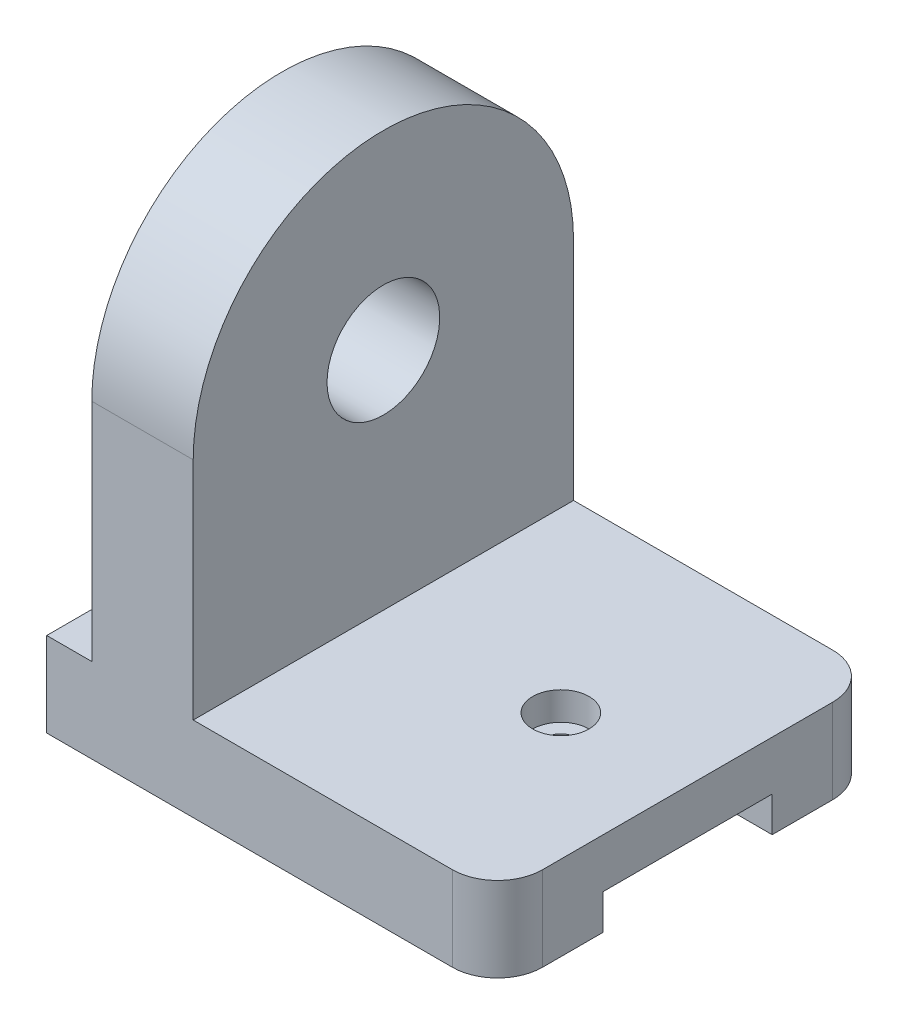
SolidWorks part; units mm, degrees
ref_plane "前视基准面" through (0, 0, 0) normal (0, 0, 1) x (1, 0, 0)
ref_plane "上视基准面" through (0, 0, 0) normal (0, 1, 0) x (1, 0, 0)
ref_plane "右视基准面" through (0, 0, 0) normal (1, 0, 0) x (0, 0, -1)
other "Configuration Table"
sketch "草图1" plane through (0, 0, 0) normal (0, 1, 0) x (1, 0, 0)
  line L1 (0, 0) -> (288, 0)
  line L2 (0, 0) -> (0, -270)
  line L3 (0, -270) -> (288, -270)
  line L4 (320, -32) -> (320, -238)
  arc A0 (288, -270) -> (320, -238) centre (288, -238) ccw
  arc A1 (288, 0) -> (320, -32) centre (288, -32) cw
  point P7 (320, -270)
  dimension "D3" = 32
  dimension "D1" = 320
  dimension "D2" = 270
extrude "凸台-拉伸1" add sketch "草图1" along normal blind 60
sketch "草图2" plane through (0, 0, 0) normal (0, -1, 0) x (1, 0, 0)
  line L0 (320, 238) -> (320, 32) construction
  line L1 (320, 135) -> (175.553, 135) construction
  line L2 (230, 195) -> (320, 195)
  line L3 (320, 195) -> (320, 75)
  line L4 (320, 75) -> (230, 75)
  arc A0 (230, 195) -> (230, 75) centre (230, 135) ccw
  dimension "D1" = 120
  dimension "D2" = 90
extrude "切除-拉伸1" cut sketch "草图2" against normal blind 25 and the other way through all
sketch "草图6" plane through (0, 60, 0) normal (0, 1, 0) x (1, 0, 0)
  arc A0 (230, -75) -> (230, -195) centre (230, -135) ccw construction
  arc A1 (230, -75) -> (230, -195) centre (230, -135) ccw
  point P0 (230, -135)
hole_wizard "孔1" positions "草图6" profile "草图7" legacy end condition through all
sketch "草图7" plane through (230, 60, 135) normal (1, 0, 0) x (0, 0, 1)
  line L0 (0, 0) -> (0, 60)
  line L1 (0, 60) -> (10, 60)
  line L2 (10, 60) -> (10, 20)
  line L3 (10, 20) -> (20, 20)
  line L4 (20, 20) -> (20, 0)
  line L5 (20, 0) -> (0, 0)
  line L6 (0, 110) -> (0, -10) construction
  dimension "直径" = 20
  dimension "深度" = 60
  dimension "柱坑直径" = 40
  dimension "柱坑深度" = 20
sketch "草图8" plane through (0, 0, 0) normal (-1, 0, 0) x (0, 0, 1)
  line L0 (135, 60) -> (135, 228.9276) construction
  line L1 (0, 60) -> (270, 60) construction
  line L2 (0, 60) -> (0, 220)
  line L3 (270, 60) -> (270, 220)
  line L4 (270, 220) -> (0, 220)
  line L5 (0, 60) -> (270, 60)
  arc A3 (270, 220) -> (0, 220) centre (135, 220) ccw
  dimension "D1" = 160
extrude "凸台-拉伸3" add sketch "草图8" against normal blind 72 from offset 32 offset against normal yes
sketch "草图10" plane through (32, 0, 0) normal (-1, 0, 0) x (0, 0, 1)
  line L0 (15, 220) -> (15, 75)
  line L1 (15, 75) -> (255, 75)
  line L2 (255, 75) -> (255, 220)
  line L3 (0, 220) -> (0, 60)
  line L4 (0, 60) -> (270, 60)
  line L5 (270, 60) -> (270, 220)
  line L6 (0, 220) -> (0, 60)
  line L7 (0, 60) -> (270, 60)
  line L8 (270, 60) -> (270, 220)
  arc A0 (255, 220) -> (15, 220) centre (135, 220) ccw
  arc A1 (270, 220) -> (0, 220) centre (135, 220) ccw
  arc A2 (270, 220) -> (0, 220) centre (135, 220) ccw
  circle A3 centre (135, 220) radius 40
  circle A4 centre (135, 220) radius 80
  dimension "D3" = 160
  dimension "D4" = 80
  dimension "D1" = 0
  dimension "D2" = 15
extrude "切除-拉伸3" cut sketch "草图10" against normal through all both and the other way through all contours A3
sketch "草图12" plane through (32, 0, 0) normal (-1, 0, 0) x (0, 0, 1)
  line L0 (255, 75) -> (255, 60)
  line L1 (255, 60) -> (15, 60)
  line L2 (15, 60) -> (15, 75)
  line L3 (0, 220) -> (0, 60)
  line L4 (0, 60) -> (270, 60)
  line L5 (270, 60) -> (270, 220)
  line L6 (0, 220) -> (0, 60)
  line L7 (0, 60) -> (270, 60)
  line L8 (270, 60) -> (270, 220)
  line L9 (15, 220) -> (15, 75)
  line L10 (15, 75) -> (255, 75)
  line L11 (255, 75) -> (255, 220)
  line L12 (15, 220) -> (15, 75)
  line L14 (255, 75) -> (255, 220)
  circle A1 centre (135, 220) radius 80
  circle A2 centre (135, 220) radius 80
  circle A3 centre (135, 220) radius 40
  circle A4 centre (135, 220) radius 40
  arc A5 (270, 220) -> (0, 220) centre (135, 220) ccw
  arc A6 (270, 220) -> (0, 220) centre (135, 220) ccw
  arc A7 (255, 220) -> (15, 220) centre (135, 220) ccw
  arc A8 (255, 220) -> (15, 220) centre (135, 220) ccw
  dimension "D1" = 0
  dimension "D2" = 0
  dimension "D3" = 0
  dimension "D4" = 0
extrude "切除-拉伸5" cut sketch "草图12" against normal blind 20
